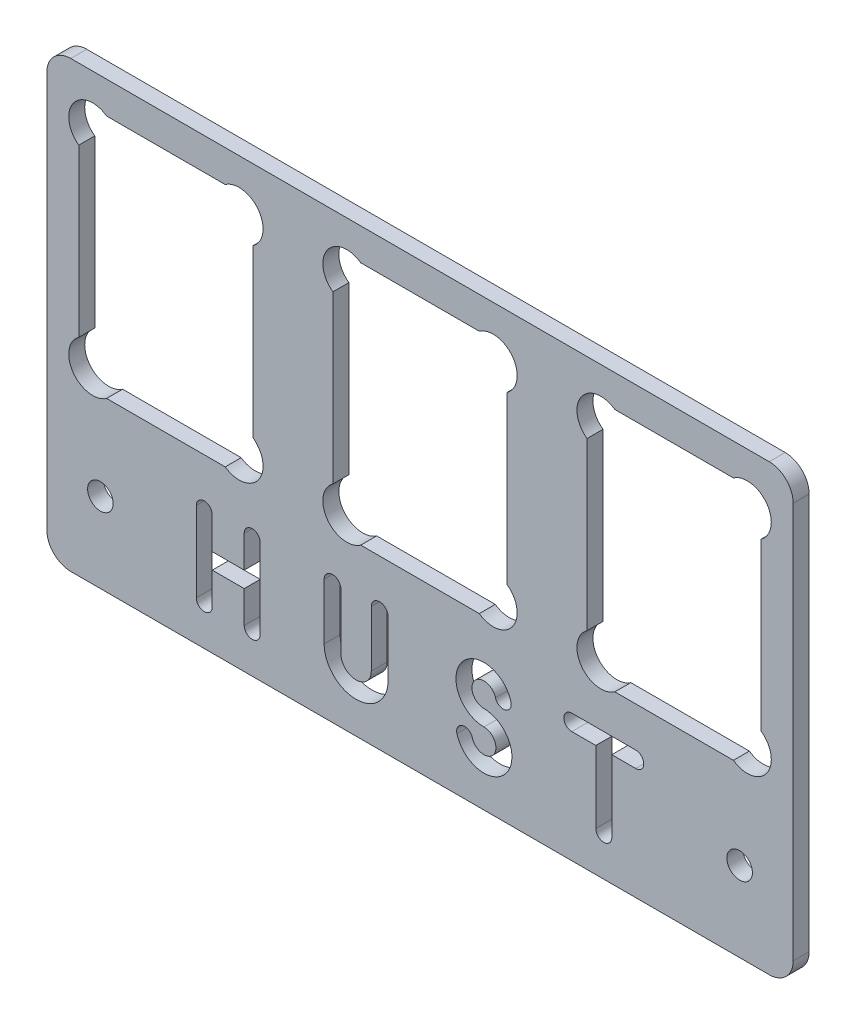
SolidWorks part; units mm, degrees
material "碳板"
ref_plane "前视基准面" through (0, 0, 0) normal (0, 0, 1) x (1, 0, 0)
ref_plane "上视基准面" through (0, 0, 0) normal (0, 1, 0) x (1, 0, 0)
ref_plane "右视基准面" through (0, 0, 0) normal (1, 0, 0) x (0, 0, -1)
sketch "草图1" plane through (0, 0, 0) normal (0, 0, 1) x (1, 0, 0)
  line L0 (-138.1669, 0) -> (160.8189, 0) construction
  line L1 (0, 122.9765) -> (0, -98.559) construction
  line L3 (-42.7, 15.3) -> (-20.9, 15.3)
  line L4 (-42.7, 15.3) -> (-42.7, -15.3)
  line L5 (-42.7, -15.3) -> (-20.9, -15.3)
  line L6 (-20.9, 15.3) -> (-20.9, -15.3)
  line L7 (-42.7, 15.3) -> (-20.9, -15.3) construction
  line L8 (-42.7, -15.3) -> (-20.9, 15.3) construction
  line L28 (-10.9, 15.3) -> (-10.9, -15.3)
  line L29 (-10.9, 15.3) -> (10.9, 15.3)
  line L30 (10.9, 15.3) -> (10.9, -15.3)
  line L31 (-10.9, -15.3) -> (10.9, -15.3)
  line L32 (20.9, 15.3) -> (20.9, -15.3)
  line L33 (20.9, 15.3) -> (42.7, 15.3)
  line L34 (42.7, 15.3) -> (42.7, -15.3)
  line L35 (20.9, -15.3) -> (42.7, -15.3)
  line L36 (-66.9969, -26.3) -> (54.405, -26.3) construction
  line L37 (-46.7, -36.3) -> (46.7, -36.3)
  line L38 (-46.7, -36.3) -> (-46.7, 19.3)
  line L39 (-46.7, 19.3) -> (46.7, 19.3)
  line L40 (46.7, -36.3) -> (46.7, 19.3)
  line L41 (-46.7, -36.3) -> (46.7, 19.3) construction
  line L42 (-46.7, 19.3) -> (46.7, -36.3) construction
  circle A0 centre (-40.9593, 12.8566) radius 3
  circle A1 centre (-22.6407, 12.8566) radius 3
  circle A2 centre (-22.6407, -12.8566) radius 3
  circle A3 centre (-40.9593, -12.8566) radius 3
  circle A18 centre (-9.1593, -12.8566) radius 3
  circle A19 centre (-9.1593, 12.8566) radius 3
  circle A20 centre (9.1593, 12.8566) radius 3
  circle A21 centre (9.1593, -12.8566) radius 3
  circle A22 centre (22.6407, -12.8566) radius 3
  circle A23 centre (22.6407, 12.8566) radius 3
  circle A24 centre (40.9593, 12.8566) radius 3
  circle A25 centre (40.9593, -12.8566) radius 3
  circle A26 centre (-40, -26.3) radius 1.6
  circle A27 centre (40, -26.3) radius 1.6
  point P5 (-31.8, 0)
  point P19 (0, -8.5)
  point P63 (-96, 0)
  dimension "D1" = 6
  dimension "D5" = 4
  dimension "D8" = 10
  dimension "D9" = 3.2
  dimension "D2" = 21.8
  dimension "D3" = 30.6
  dimension "D6" = 4
  dimension "D7" = 21
  dimension "D10" = 80
  dimension "D11" = 10
  dimension "D4" = 3
extrude "凸台-拉伸1" add sketch "草图1" along normal blind 2
sketch "草图2" plane through (0, 0, 2) normal (0, 0, 1) x (1, 0, 0)
  line L0 (0, 8.4462) -> (0, -46.993) construction
  line L1 (-40, -26.3) -> (40, -26.3) construction
  line L2 (-28, -31.3) -> (-28, -21.3)
  line L3 (-22, -27.3) -> (-22, -31.3)
  line L4 (-26, -21.3) -> (-26, -25.3)
  line L5 (-26, -25.3) -> (-22, -25.3)
  line L6 (-22, -25.3) -> (-22, -21.3)
  line L7 (-26, -27.3) -> (-22, -27.3)
  line L8 (-20, -21.3) -> (-20, -31.3)
  line L9 (-26, -31.3) -> (-26, -27.3)
  line L10 (-21, -32.3) -> (-3.3811, -32.3) construction
  line L11 (19, -21.3) -> (27, -21.3) construction
  line L12 (-10.95, -21.3) -> (-10.95, -28.3) construction
  line L13 (-5.05, -28.3) -> (-5.05, -21.3) construction
  line L14 (-12, -21.3) -> (-12, -28.3)
  line L15 (-4, -28.3) -> (-4, -21.3)
  line L16 (-9.9, -21.3) -> (-9.9, -28.3)
  line L17 (-6.1, -28.3) -> (-6.1, -21.3)
  line L18 (23, -21.3) -> (23, -31.3) construction
  line L19 (19, -22.3) -> (22, -22.3)
  line L20 (22, -22.3) -> (22, -31.3)
  line L21 (19, -20.3) -> (27, -20.3)
  line L22 (24, -22.3) -> (24, -31.3)
  line L23 (24, -22.3) -> (27, -22.3)
  line L24 (22, -26.4508) -> (22, -31.3) construction
  line L25 (24, -26.4508) -> (24, -31.3) construction
  line L26 (23, -26.4508) -> (23, -31.3) construction
  line L27 (19, -22.3) -> (27, -22.3) construction
  line L28 (8, -23.8) -> (10.4148, -23.153) construction
  line L29 (8, -28.8) -> (5.5852, -29.447) construction
  arc A0 (-26, -21.3) -> (-28, -21.3) centre (-27, -21.3) ccw
  arc A1 (-20, -21.3) -> (-22, -21.3) centre (-21, -21.3) ccw
  arc A2 (-20, -31.3) -> (-22, -31.3) centre (-21, -31.3) cw
  arc A3 (-26, -31.3) -> (-28, -31.3) centre (-27, -31.3) cw
  arc A4 (-10.95, -28.3) -> (-5.05, -28.3) centre (-8, -28.3) ccw construction
  arc A5 (-12, -28.3) -> (-4, -28.3) centre (-8, -28.3) ccw
  arc A6 (-9.9, -28.3) -> (-6.1, -28.3) centre (-8, -28.3) ccw
  arc A7 (-9.9, -21.3) -> (-12, -21.3) centre (-10.95, -21.3) ccw
  arc A8 (-4, -21.3) -> (-6.1, -21.3) centre (-5.05, -21.3) ccw
  arc A9 (-10.95, -28.3) -> (-5.05, -28.3) centre (-8, -28.3) ccw construction
  arc A10 (19, -20.3) -> (19, -22.3) centre (19, -21.3) ccw
  arc A11 (27, -22.3) -> (27, -20.3) centre (27, -21.3) ccw
  arc A12 (22, -31.3) -> (24, -31.3) centre (23, -31.3) ccw
  arc A13 (8, -26.3) -> (10.4148, -23.153) centre (8, -23.8) cw construction
  arc A14 (8, -26.3) -> (5.5852, -29.447) centre (8, -28.8) cw construction
  arc A15 (8, -25.3) -> (4.6193, -29.7059) centre (8, -28.8) cw
  arc A16 (8, -25.3) -> (9.4489, -23.4118) centre (8, -23.8) cw
  arc A17 (8, -27.3) -> (6.5511, -29.1882) centre (8, -28.8) cw
  arc A18 (8, -27.3) -> (11.3807, -22.8941) centre (8, -23.8) cw
  arc A19 (6.5511, -29.1882) -> (4.6193, -29.7059) centre (5.5852, -29.447) ccw
  arc A20 (9.4489, -23.4118) -> (11.3807, -22.8941) centre (10.4148, -23.153) ccw
  point P19 (-20, -26.3)
  point P26 (-28, -26.3)
  dimension "D1" = 2
  dimension "D6" = 1.05
  dimension "D8" = 8
  dimension "D11" = 13
  dimension "D12" = 8
  dimension "D14" = 15
  dimension "D2" = 2
  dimension "D3" = 10
  dimension "D4" = 8
  dimension "D5" = 12
  dimension "D7" = 8
  dimension "D9" = 8
  dimension "D15" = 15
  dimension "D10" = 1
  dimension "D13" = 1
extrude "切除-拉伸1" cut sketch "草图2" against normal through all
fillet "圆角1" radius 3 4 edges at (-46.7, 19.3, 1) (46.7, 19.3, 1) (46.7, -36.3, 1) (-46.7, -36.3, 1)
